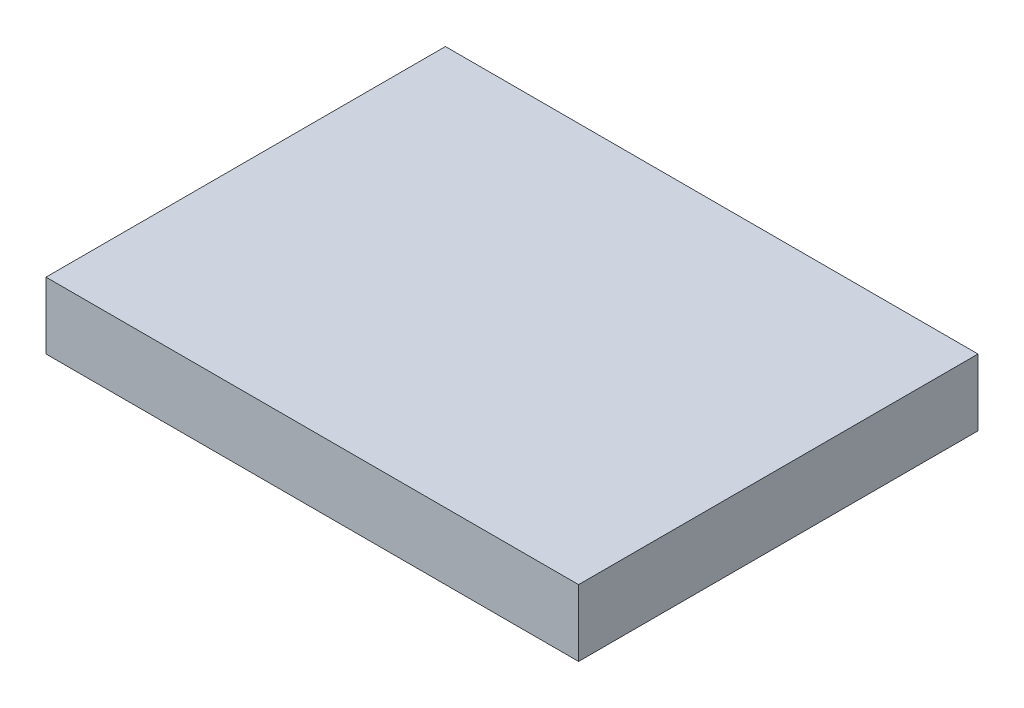
SolidWorks part; units mm, degrees
ref_plane "Front Plane" through (0, 0, 0) normal (0, 0, 1) x (1, 0, 0)
ref_plane "Top Plane" through (0, 0, 0) normal (0, 1, 0) x (1, 0, 0)
ref_plane "Right Plane" through (0, 0, 0) normal (1, 0, 0) x (0, 0, -1)
sketch "Sketch14" plane through (0, 0, 0) normal (0, 1, 0) x (1, 0, 0)
  line L1 (0, 0) -> (101.6, 0)
  line L2 (0, 0) -> (0, 76.2)
  line L3 (0, 76.2) -> (101.6, 76.2)
  line L4 (101.6, 0) -> (101.6, 76.2)
  dimension "D1" = 76.2
  dimension "D2" = 101.6
extrude "Extrude6" add sketch "Sketch14" against normal blind 12.7
ref_plane "Plane5" through (0, 0, -38.1) normal (0, 0, 1) x (1, 0, 0)
sketch "Sketch16" plane through (0, 0, -38.1) normal (0, 0, 1) x (1, 0, 0)
  line L0 (36.6946, 0) -> (36.6946, 25.1978) construction
  line L1 (30.7188, 0) -> (16.3347, 0)
  line L2 (0, 0) -> (101.6, 0) construction
  line L3 (16.3347, 0) -> (16.3347, -3.2635)
  line L4 (30.7188, 0) -> (36.6946, 0) construction
